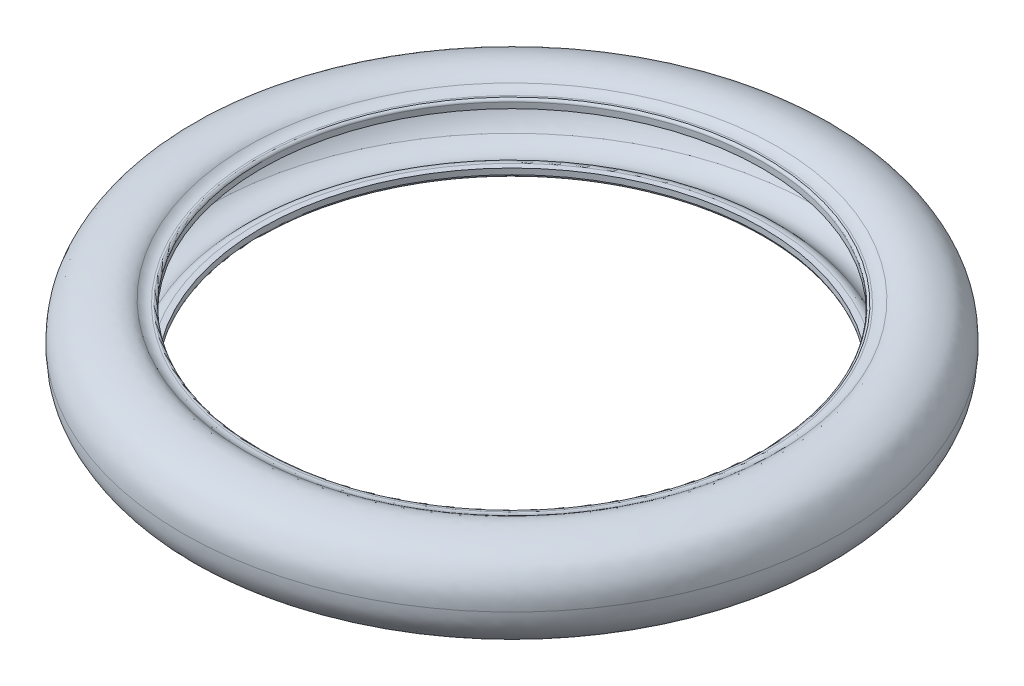
SolidWorks part; units mm, degrees
material "Rubber"
ref_plane "Front Plane" through (0, 0, 0) normal (0, 0, 1) x (1, 0, 0)
ref_plane "Top Plane" through (0, 0, 0) normal (0, 1, 0) x (1, 0, 0)
ref_plane "Right Plane" through (0, 0, 0) normal (1, 0, 0) x (0, 0, -1)
sketch "Sketch2" plane through (0, 0, 0) normal (0, 0, 1) x (1, 0, 0)
  line L22 (82.2312, 16.5641) -> (80.7312, 16.5641)
  line L24 (82.2312, 12.5641) -> (80.7312, 12.5641)
  line L25 (78.7312, 27.8158) -> (78.7312, 18.5641)
  line L26 (74.7312, 27.8158) -> (74.7312, 18.5641)
  line L27 (78.7312, 69.5641) -> (78.7312, 63.8123)
  line L28 (82.2312, 71.5641) -> (80.7312, 71.5641)
  line L29 (92.5312, 78.5293) -> (92.5312, 78.3579)
  line L30 (82.2312, 75.5641) -> (80.8237, 75.5641)
  line L31 (74.9149, 70.606) -> (73.6351, 63.3479)
  line L32 (63.9337, 45.962) -> (46.0799, 33.4606)
  line L33 (61.7543, 42.849) -> (46.8255, 32.3957)
  line L34 (-40.5799, 30.4422) -> (27.8256, 28.0535)
  line L35 (-24.6668, 28.5857) -> (27.7802, 26.7542)
  line L36 (-70.0688, 26.0641) -> (-34.7483, 26.0641)
  line L37 (-62.0688, 30.5641) -> (-47.5598, 30.5641)
  line L38 (-72.0688, 24.0641) -> (-72.0688, 7.5641)
  line L39 (-77.0688, 28.5641) -> (-77.0688, 7.5641)
  line L40 (-75.0688, 30.5641) -> (-70.0688, 30.5641)
  line L41 (92.5312, 9.7702) -> (92.5312, 78.3579) construction
  line L42 (92.5312, 44.0641) -> (-124.0688, 44.0641) construction
  line L44 (-77.0688, 7.5641) -> (-72.0688, 7.5641)
  line L45 (-124.0688, 89.0641) -> (-124.0688, -22.0503) construction
  line L46 (92.5312, 9.7702) -> (92.5312, 9.5988)
  line L47 (-70.0688, 30.5641) -> (-62.0688, 30.5641)
  arc A30 (89.2067, 8.9212) -> (82.2312, 12.5641) centre (82.2312, 4.0641) ccw
  arc A31 (89.2067, 8.9212) -> (91.5807, 8.2031) centre (90.848, 10.0641) ccw
  arc A32 (91.5807, 8.2031) -> (92.5312, 9.5988) centre (91.0312, 9.5988) ccw
  arc A33 (92.5312, 9.7702) -> (91.4959, 12.4554) centre (88.5312, 9.7702) ccw
  arc A34 (91.4959, 12.4554) -> (82.2312, 16.5641) centre (82.2312, 4.0641) ccw
  arc A35 (78.7312, 18.5641) -> (80.7312, 16.5641) centre (80.7312, 18.5641) ccw
  arc A36 (74.7312, 18.5641) -> (80.7312, 12.5641) centre (80.7312, 18.5641) ccw
  arc A37 (78.7312, 27.8158) -> (75.6008, 34.163) centre (70.7312, 27.8158) ccw
  arc A38 (74.7312, 27.8158) -> (73.166, 30.9894) centre (70.7312, 27.8158) ccw
  arc A39 (66.3736, 41.1651) -> (73.166, 30.9894) centre (84.7312, 46.0641) ccw
  arc A40 (75.8676, 58.1651) -> (75.6008, 34.163) centre (84.7312, 46.0641) ccw
  arc A41 (66.3736, 41.1651) -> (61.7543, 42.849) centre (63.4751, 40.3915) ccw
  arc A42 (75.8676, 58.1651) -> (78.7312, 63.8123) centre (71.7312, 63.8123) ccw
  arc A43 (80.7312, 71.5641) -> (78.7312, 69.5641) centre (80.7312, 69.5641) ccw
  arc A44 (82.2312, 71.5641) -> (91.4959, 75.6727) centre (82.2312, 84.0641) ccw
  arc A45 (91.4959, 75.6727) -> (92.5312, 78.3579) centre (88.5312, 78.3579) ccw
  arc A46 (92.5312, 78.5293) -> (91.5807, 79.925) centre (91.0312, 78.5293) ccw
  arc A47 (91.5807, 79.925) -> (89.2067, 79.2069) centre (90.848, 78.0641) ccw
  arc A48 (80.8237, 75.5641) -> (74.9149, 70.606) centre (80.8237, 69.5641) ccw
  arc A49 (82.2312, 75.5641) -> (89.2067, 79.2069) centre (82.2312, 84.0641) ccw
  arc A50 (71.8074, 59.9916) -> (73.6351, 63.3479) centre (67.7263, 64.3898) ccw
  arc A51 (71.8074, 59.9916) -> (65.9961, 49.2257) centre (84.7312, 46.0641) ccw
  arc A52 (63.9337, 45.962) -> (65.9961, 49.2257) centre (61.0658, 50.0578) ccw
  arc A53 (27.7802, 26.7542) -> (46.8255, 32.3957) centre (28.8726, 58.0352) ccw
  arc A54 (27.8256, 28.0535) -> (46.0799, 33.4606) centre (28.8726, 58.0352) ccw
  arc A55 (-24.6668, 28.5857) -> (-29.8821, 27.3279) centre (-25.0158, 18.5918) ccw
  arc A56 (-34.7483, 26.0641) -> (-29.8821, 27.3279) centre (-34.7483, 36.0641) ccw
  arc A57 (-40.5799, 30.4422) -> (-47.5598, 30.5641) centre (-47.5598, -169.4359) ccw
  arc A58 (-70.0688, 26.0641) -> (-72.0688, 24.0641) centre (-70.0688, 24.0641) ccw
  arc A59 (-75.0688, 30.5641) -> (-77.0688, 28.5641) centre (-75.0688, 28.5641) ccw
ref_plane "New Right Plane" through (-124.0688, 0, 0) normal (-1, 0, 0) x (0, 0, 1)
ref_plane "New Top Plane" through (0, 44.0641, 0) normal (0, 1, 0) x (-1, 0, 0)
sketch "Sketch3" plane through (0, 0, 0) normal (0, 0, 1) x (1, 0, 0)
  line L6 (82.2312, 71.5641) -> (80.7312, 71.5641)
  line L7 (78.7312, 69.5641) -> (78.7312, 64.8641)
  line L8 (83.4049, 64.8641) -> (78.7312, 64.8641)
  line L9 (82.2312, 16.5641) -> (80.7312, 16.5641)
  line L10 (78.7312, 18.5641) -> (78.7312, 23.2641)
  line L11 (83.4049, 23.2641) -> (78.7312, 23.2641)
  line L12 (142.6312, 97.3384) -> (142.6312, -20.4458) construction
  line L13 (-124.0688, 89.0641) -> (-124.0688, -22.0503) construction
  line L14 (-124.0688, 44.0641) -> (210.2552, 44.0641) construction
  line L15 (142.6312, 39.0388) -> (142.6312, 49.0894) construction
  arc A28 (106.3833, 78.8046) -> (93.5924, 76.4811) centre (106.924, 39.4584) ccw construction
  arc A29 (93.5924, 76.4811) -> (90.4252, 74.6243) centre (96.9804, 67.0725) ccw construction
  arc A30 (82.2312, 71.5641) -> (90.4252, 74.6243) centre (82.2312, 84.0641) ccw
  arc A31 (80.7312, 71.5641) -> (78.7312, 69.5641) centre (80.7312, 69.5641) ccw
  arc A32 (83.4049, 64.8641) -> (91.0723, 68.4444) centre (83.4049, 74.8641) ccw
  arc A33 (121.9283, 71.0415) -> (91.0723, 68.4444) centre (107.7875, 54.4493) ccw
  arc A34 (115.5771, 77.2104) -> (106.3833, 78.8046) centre (105.3914, 45.7764) ccw construction
  arc A35 (121.5483, 74.0812) -> (115.5771, 77.2104) centre (109.412, 58.1843) ccw construction
  arc A36 (125.8951, 70.7308) -> (121.5483, 74.0812) centre (-239.2277, -398.4844) ccw construction
  arc A37 (130.9922, 54.571) -> (121.9283, 71.0415) centre (95.5563, 45.7995) ccw
  arc A38 (130.8319, 65.1199) -> (125.8951, 70.7308) centre (113.6125, 54.9467) ccw construction
  arc A39 (134.2733, 54.9239) -> (130.8319, 65.1199) centre (108.4105, 51.8733) ccw construction
  arc A40 (131.848, 44.0641) -> (130.9922, 54.571) centre (68.6139, 44.2018) ccw
  arc A41 (134.848, 44.0641) -> (134.2733, 54.9239) centre (34.5651, 44.2019) ccw construction
  arc A42 (134.2733, 33.2043) -> (134.848, 44.0641) centre (34.5651, 43.9262) ccw construction
  arc A43 (130.9922, 33.5571) -> (131.848, 44.0641) centre (68.6139, 43.9263) ccw
  arc A44 (121.9283, 17.0866) -> (130.9922, 33.5571) centre (95.5563, 42.3287) ccw
  arc A45 (130.8319, 23.0083) -> (134.2733, 33.2043) centre (108.4105, 36.2548) ccw construction
  arc A46 (125.8951, 17.3973) -> (130.8319, 23.0083) centre (113.6125, 33.1814) ccw construction
  arc A47 (121.5483, 14.047) -> (125.8951, 17.3973) centre (-239.2277, 486.6125) ccw construction
  arc A48 (115.5771, 10.9177) -> (121.5483, 14.047) centre (109.412, 29.9438) ccw construction
  arc A49 (91.0723, 19.6837) -> (121.9283, 17.0866) centre (107.7875, 33.6788) ccw
  arc A50 (106.3833, 9.3235) -> (115.5771, 10.9177) centre (105.3914, 42.3517) ccw construction
  arc A51 (93.5924, 11.647) -> (106.3833, 9.3235) centre (106.924, 48.6698) ccw construction
  arc A52 (90.4252, 13.5038) -> (93.5924, 11.647) centre (96.9804, 21.0556) ccw construction
  arc A53 (90.4252, 13.5038) -> (82.2312, 16.5641) centre (82.2312, 4.0641) ccw
  arc A54 (78.7312, 18.5641) -> (80.7312, 16.5641) centre (80.7312, 18.5641) ccw
  arc A55 (91.0723, 19.6837) -> (83.4049, 23.2641) centre (83.4049, 13.2641) ccw
  spline S0 degree 3 poles (90.4252, 74.6243) (93.4535, 77.253) (104.0992, 79.9741) (115.4204, 77.9769) (124.5325, 75.1463) (131.714, 71.8996) (137.278, 64.4636) (139.549, 60.6335) (142.2345, 53.4872) (142.6312, 48.4486) (142.6312, 44.0641) knots 0 0 0 0 0.186434 0.396888 0.443717 0.631279 0.6736 0.824603 0.85913 1 1 1 1
  spline S1 degree 3 poles (90.4252, 13.5038) (93.4535, 10.8751) (104.0992, 8.154) (115.4204, 10.1512) (124.5325, 12.9818) (131.714, 16.2285) (137.278, 23.6646) (139.549, 27.4946) (142.2345, 34.641) (142.6312, 39.6795) (142.6312, 44.0641) knots 0 0 0 0 0.186434 0.396888 0.443717 0.631279 0.6736 0.824603 0.85913 1 1 1 1
  dimension "D1" = 266.7
revolve "Revolve1" add sketch "Sketch3" angle 360 about L45
